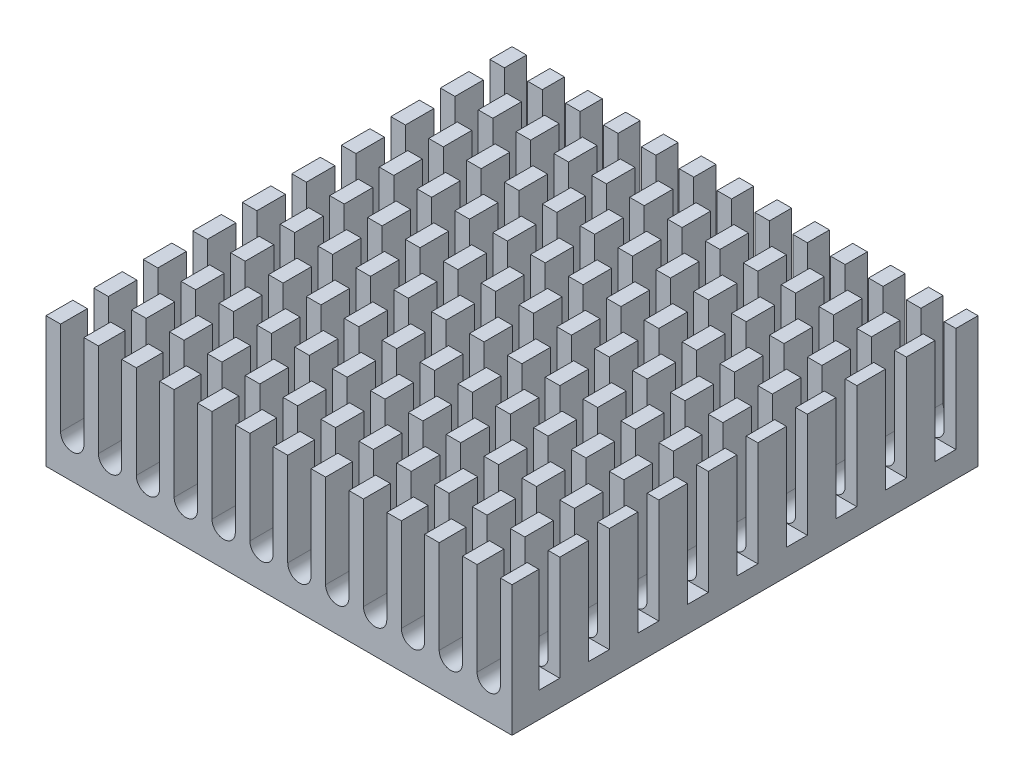
SolidWorks part; units mm, degrees
ref_plane "Front Plane" through (0, 0, 0) normal (0, 0, 1) x (1, 0, 0)
ref_plane "Top Plane" through (0, 0, 0) normal (0, 1, 0) x (1, 0, 0)
ref_plane "Right Plane" through (0, 0, 0) normal (1, 0, 0) x (0, 0, -1)
sketch "Sketch1" plane through (0, 0, 0) normal (0, 1, 0) x (1, 0, 0)
  line L1 (20, -20) -> (-20, -20)
  line L2 (20, -20) -> (20, 20)
  line L3 (20, 20) -> (-20, 20)
  line L4 (-20, -20) -> (-20, 20)
  line L5 (20, -20) -> (-20, 20) construction
  line L6 (20, 20) -> (-20, -20) construction
  point P0 (0, 0)
  dimension "D1" = 40
  dimension "D2" = 40
extrude "Boss-Extrude1" add sketch "Sketch1" along normal blind 11.2
sketch "Sketch2" plane through (0, 0, 20) normal (0, 0, 1) x (1, 0, 0)
  line L0 (17, 3.2) -> (17, 11.2)
  line L1 (-20, 11.2) -> (20, 11.2) construction
  line L2 (17, 11.2) -> (19, 11.2)
  line L3 (19, 11.2) -> (19, 3.2)
  line L4 (-1009.2514, 2.2) -> (48990.7486, 2.2) construction
  line L5 (20, 11.2) -> (20, 0) construction
  arc A0 (17, 3.2) -> (19, 3.2) centre (18, 3.2) ccw
  dimension "D1" = 2
  dimension "D2" = 9
  dimension "D3" = 1
extrude "Cut-Extrude1" cut sketch "Sketch2" against normal through all
pattern_linear "LPattern1" count 12 spacing 3.25 along (-1, 0, 0) of "Cut-Extrude1"
sketch "Sketch3" plane through (20, 0, 0) normal (1, 0, 0) x (0, 0, -1)
  line L0 (-20, 11.2) -> (20, 11.2) construction
  line L1 (-17.7, 11.2) -> (-15.9, 11.2)
  line L2 (-17.7, 11.2) -> (-17.7, 2.2)
  line L3 (-17.7, 2.2) -> (-15.9, 2.2)
  line L4 (-15.9, 11.2) -> (-15.9, 2.2)
  line L5 (-20, 11.2) -> (-20, 0) construction
  dimension "D1" = 1.8
  dimension "D2" = 2.3
  dimension "D3" = 9
extrude "Cut-Extrude2" cut sketch "Sketch3" against normal through all
pattern_linear "LPattern2" count 9 spacing 4.25 along (0, 0, -1) of "Cut-Extrude2"
